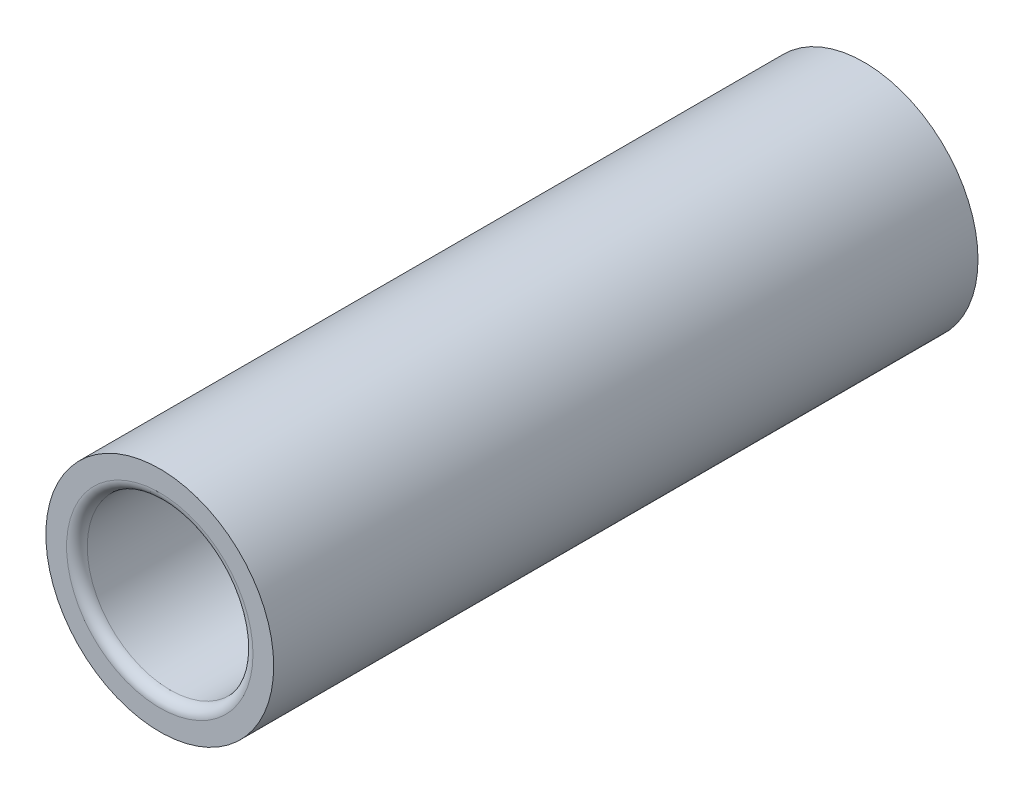
SolidWorks part; units mm, degrees
material "Teak"
ref_plane "Plano frontal" through (0, 0, 0) normal (0, 0, 1) x (1, 0, 0)
ref_plane "Plano superior" through (0, 0, 0) normal (0, 1, 0) x (1, 0, 0)
ref_plane "Plano direito" through (0, 0, 0) normal (1, 0, 0) x (0, 0, -1)
sketch "Sketch1" plane through (0, 0, 0) normal (0, 0, 1) x (1, 0, 0)
  circle A0 centre (0, 0) radius 8
  circle A1 centre (0, 0) radius 11
  dimension "D1" = 22
  dimension "D2" = 16
extrude "Boss-Extrude1" add sketch "Sketch1" along normal mid plane 68
fillet "Fillet1" radius 1 2 edges at (8, 0, -34) (8, 0, 34)
